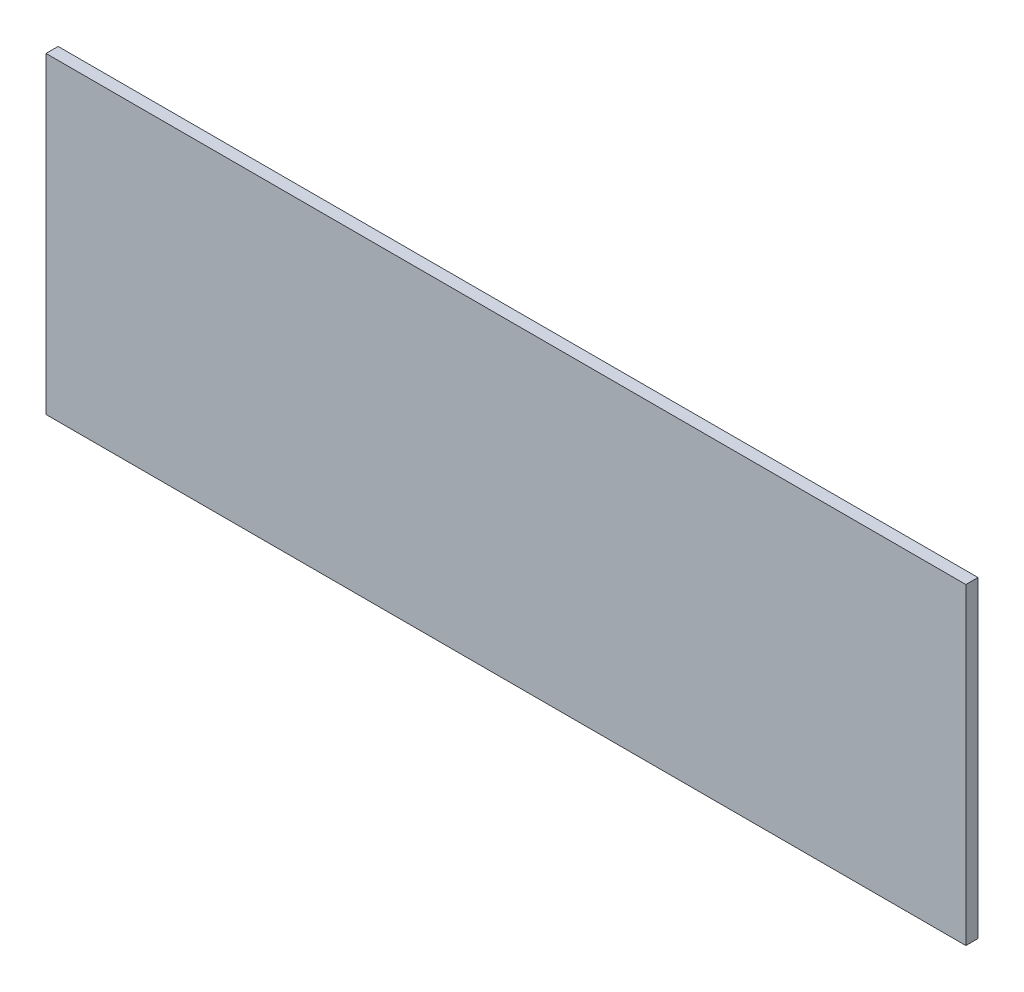
SolidWorks part; units mm, degrees
ref_plane "Plan de face" through (0, 0, 0) normal (0, 0, 1) x (1, 0, 0)
ref_plane "Plan de dessus" through (0, 0, 0) normal (0, 1, 0) x (1, 0, 0)
ref_plane "Plan de droite" through (0, 0, 0) normal (1, 0, 0) x (0, 0, -1)
sketch "Esquisse1" plane through (0, 0, 0) normal (0, 0, 1) x (1, 0, 0)
  line L1 (-151.5, -51.5) -> (151.5, -51.5)
  line L2 (-151.5, -51.5) -> (-151.5, 51.5)
  line L3 (-151.5, 51.5) -> (151.5, 51.5)
  line L4 (151.5, -51.5) -> (151.5, 51.5)
  line L5 (-151.5, -51.5) -> (151.5, 51.5) construction
  line L6 (-151.5, 51.5) -> (151.5, -51.5) construction
  point P0 (0, 0)
  dimension "D1" = 103
  dimension "D2" = 303
extrude "Boss.-Extru.1" add sketch "Esquisse1" along normal blind 4
